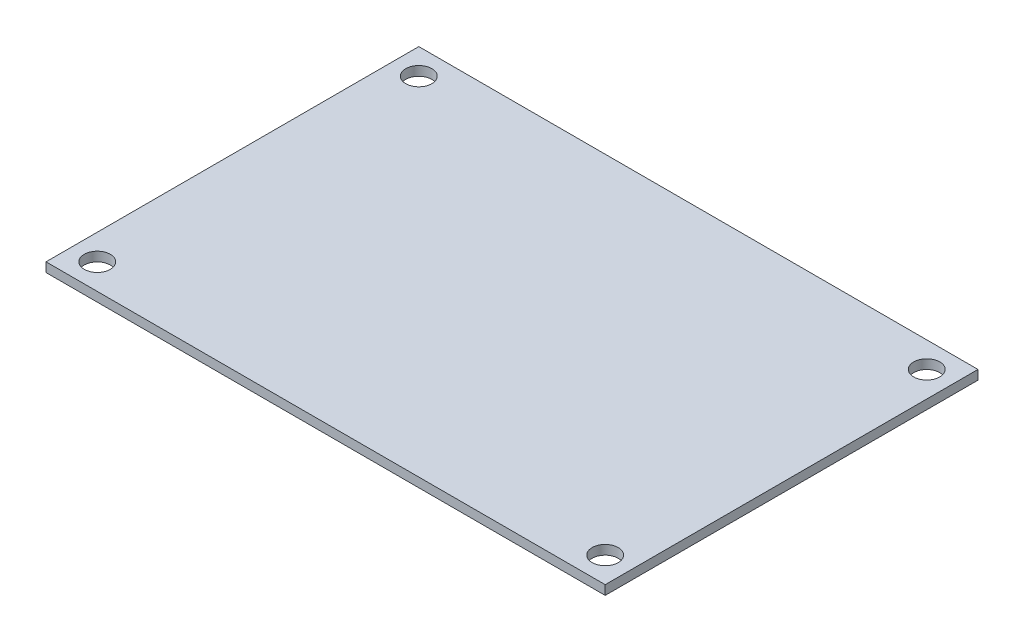
SolidWorks part; units mm, degrees
ref_plane "Front Plane" through (0, 0, 0) normal (0, 0, 1) x (1, 0, 0)
ref_plane "Top Plane" through (0, 0, 0) normal (0, 1, 0) x (1, 0, 0)
ref_plane "Right Plane" through (0, 0, 0) normal (1, 0, 0) x (0, 0, -1)
sketch "Sketch1" plane through (0, 0, 0) normal (0, 1, 0) x (1, 0, 0)
  line L1 (0, 0) -> (60, 0)
  line L2 (0, 0) -> (0, 40)
  line L3 (0, 40) -> (60, 40)
  line L4 (60, 0) -> (60, 40)
  dimension "D1" = 60
  dimension "D2" = 40
extrude "Boss-Extrude1" add sketch "Sketch1" along normal blind 1
sketch "Sketch2" plane through (0, 1, 0) normal (0, 1, 0) x (1, 0, 0)
  line L0 (2.75, 20) -> (0, 20) construction
  line L1 (2.75, 37.25) -> (57.25, 37.25) construction
  line L2 (2.75, 37.25) -> (2.75, 2.75) construction
  line L3 (2.75, 2.75) -> (57.25, 2.75) construction
  line L4 (57.25, 37.25) -> (57.25, 2.75) construction
  line L5 (0, 40) -> (0, 0) construction
  line L6 (30, 37.25) -> (30, 40) construction
  line L7 (60, 40) -> (0, 40) construction
  line L8 (30, 0) -> (30, 2.75) construction
  line L9 (0, 0) -> (60, 0) construction
  line L10 (57.25, 20) -> (60, 20) construction
  line L11 (60, 0) -> (60, 40) construction
  circle A0 centre (2.75, 37.25) radius 1.4
  circle A1 centre (57.25, 37.25) radius 1.4
  circle A2 centre (57.25, 2.75) radius 1.4
  circle A3 centre (2.75, 2.75) radius 1.4
  dimension "D3" = 2.8
  dimension "D1" = 54.5
  dimension "D2" = 34.5
extrude "Cut-Extrude1" cut sketch "Sketch2" against normal through all
